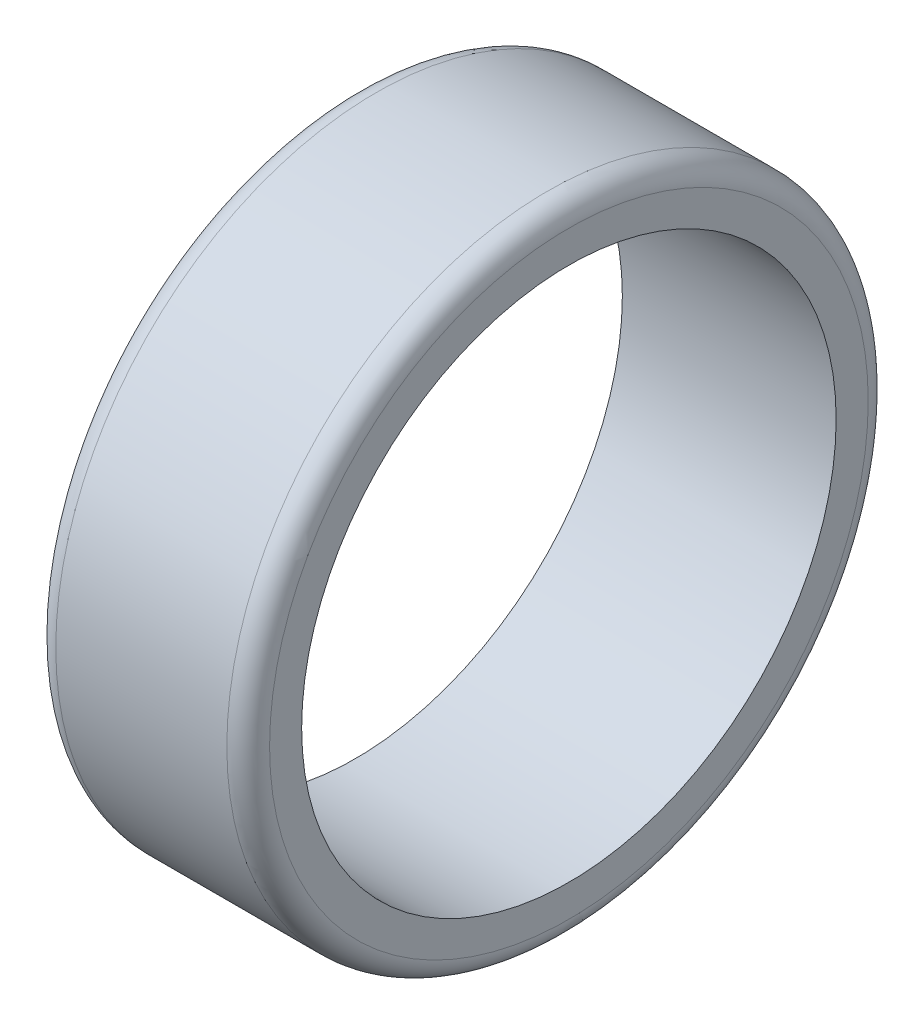
SolidWorks part; units mm, degrees
ref_plane "Front Plane" through (0, 0, 0) normal (0, 0, 1) x (1, 0, 0)
ref_plane "Top Plane" through (0, 0, 0) normal (0, 1, 0) x (1, 0, 0)
ref_plane "Right Plane" through (0, 0, 0) normal (1, 0, 0) x (0, 0, -1)
sketch "Sketch1" plane through (0, 0, 0) normal (0, 0, 1) x (1, 0, 0)
  line L0 (0, 0) -> (16, 0) construction
  line L1 (8, 0) -> (8, 15) construction
  line L2 (3, 15) -> (13, 15)
  line L3 (3, 15) -> (3, 12.5)
  line L4 (3, 12.5) -> (13, 12.5)
  line L5 (13, 15) -> (13, 12.5)
  dimension "W" = 16
  dimension "D" = 30
  dimension "B" = 10
  dimension "T" = 2.5
revolve "Revolve1" add sketch "Sketch1" angle 360 about L0
fillet "Fillet1" radius 1 2 edges at (3, 0, 15) (13, 0, 15)
